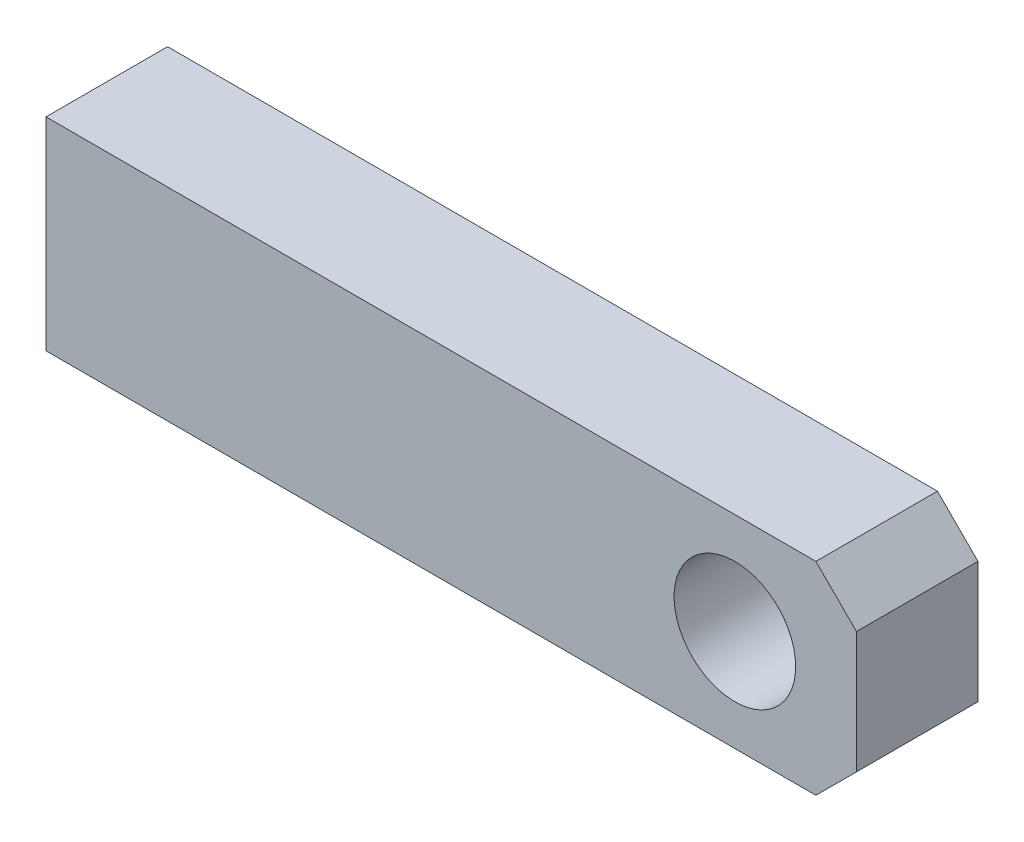
SolidWorks part; units mm, degrees
ref_plane "前视基准面" through (0, 0, 0) normal (0, 0, 1) x (1, 0, 0)
ref_plane "上视基准面" through (0, 0, 0) normal (0, 1, 0) x (1, 0, 0)
ref_plane "右视基准面" through (0, 0, 0) normal (1, 0, 0) x (0, 0, -1)
sketch "草图1" plane through (0, 0, 0) normal (0, 0, 1) x (1, 0, 0)
  line L1 (-16.4536, 2.0698) -> (3.5464, 2.0698)
  line L2 (-16.4536, 2.0698) -> (-16.4536, -2.9302)
  line L3 (-16.4536, -2.9302) -> (3.5464, -2.9302)
  line L4 (3.5464, 2.0698) -> (3.5464, -2.9302)
  line L5 (-16.4536, 2.0698) -> (3.5464, -2.9302) construction
  line L6 (-16.4536, -2.9302) -> (3.5464, 2.0698) construction
  point P0 (-6.4536, -0.4302)
  dimension "D1" = 20
  dimension "D2" = 5
extrude "凸台-拉伸1" add sketch "草图1" along normal blind 3
sketch "草图2" plane through (0, 0, 3) normal (0, 0, 1) x (1, 0, 0)
  line L0 (3.5464, -2.9302) -> (3.5464, 2.0698) construction
  line L1 (3.5464, 2.0698) -> (-16.4536, 2.0698) construction
  circle A0 centre (0.5464, -0.4302) radius 1.5
  dimension "D3" = 3
  dimension "D1" = 3
  dimension "D2" = 2.5
extrude "切除-拉伸1" cut sketch "草图2" against normal blind 3
chamfer "倒角1" distance 1 angle 45 1 edges at (3.5464, -2.9302, 1.5)
chamfer "倒角2" distance 1 angle 45 1 edges at (3.5464, 2.0698, 1.5)
